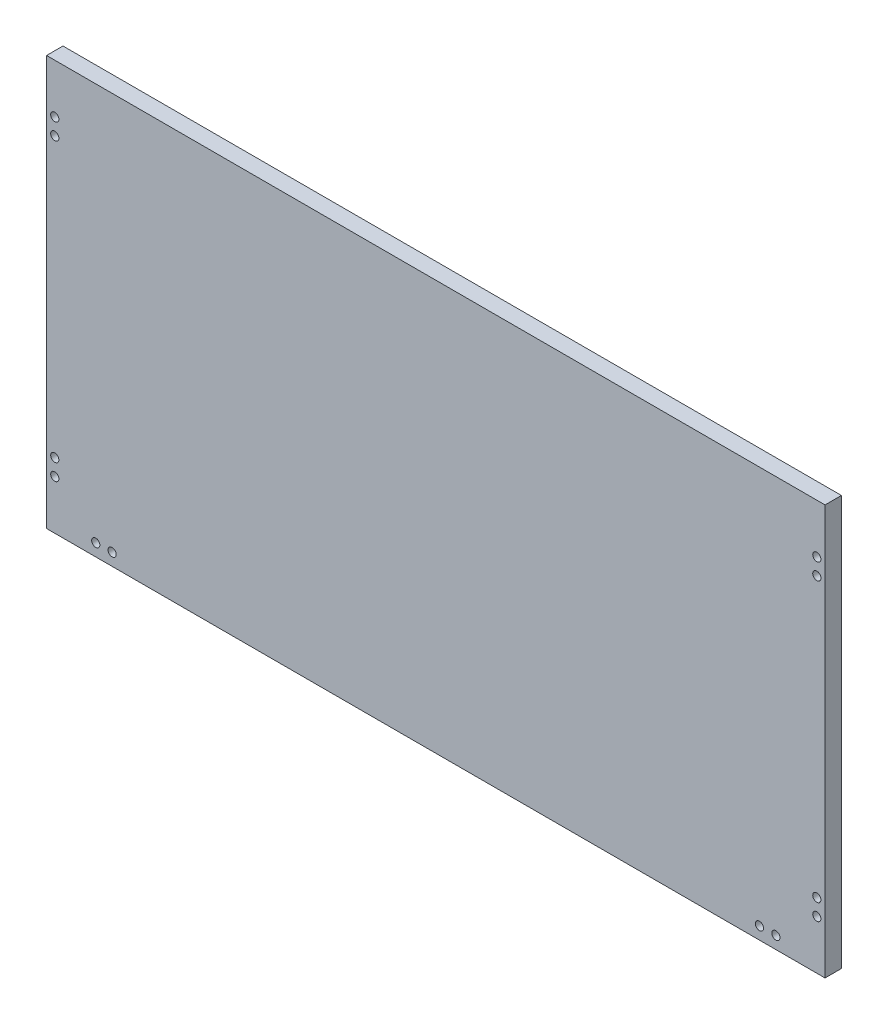
SolidWorks part; units mm, degrees
ref_plane "Front Plane" through (0, 0, 0) normal (0, 0, 1) x (1, 0, 0)
ref_plane "Top Plane" through (0, 0, 0) normal (0, 1, 0) x (1, 0, 0)
ref_plane "Right Plane" through (0, 0, 0) normal (1, 0, 0) x (0, 0, -1)
sketch "Sketch1" plane through (0, 0, 0) normal (0, 0, 1) x (1, 0, 0)
  line L1 (-237.5, 125) -> (237.5, 125)
  line L2 (-237.5, 125) -> (-237.5, -125)
  line L3 (-237.5, -125) -> (237.5, -125)
  line L4 (237.5, 125) -> (237.5, -125)
  line L5 (-237.5, 125) -> (237.5, -125) construction
  line L6 (-237.5, -125) -> (237.5, 125) construction
  point P0 (0, 0)
  dimension "D1" = 250
  dimension "D2" = 475
extrude "Boss-Extrude1" add sketch "Sketch1" along normal blind 10
sketch "Sketch2" plane through (0, 0, 10) normal (0, 0, 1) x (1, 0, 0)
  line L0 (-237.5, 125) -> (-237.5, -125) construction
  line L2 (237.5, -125) -> (237.5, 125) construction
  line L3 (-237.5, -125) -> (237.5, -125) construction
  line L4 (237.5, 125) -> (-237.5, 125) construction
  circle A0 centre (-232.5, 95) radius 2.5
  circle A1 centre (-232.5, 85) radius 2.5
  circle A2 centre (-207.5, -117.5) radius 2.5
  circle A3 centre (-197.5, -117.5) radius 2.5
  circle A4 centre (197.5, -117.5) radius 2.5
  circle A5 centre (207.5, -117.5) radius 2.5
  circle A6 centre (232.5, 95) radius 2.5
  circle A7 centre (232.5, 85) radius 2.5
  circle A8 centre (232.5, -85) radius 2.5
  circle A9 centre (232.5, -95) radius 2.5
  circle A10 centre (-232.5, -85) radius 2.5
  circle A11 centre (-232.5, -95) radius 2.5
  dimension "D1" = 5
  dimension "D2" = 30
  dimension "D3" = 10
  dimension "D4" = 10
  dimension "D5" = 30
  dimension "D6" = 7.5
  dimension "D7" = 30
  dimension "D8" = 30
  dimension "D9" = 10
  dimension "D10" = 10
  dimension "D11" = 5
  dimension "D12" = 5
extrude "Cut-Extrude1" cut sketch "Sketch2" against normal through all
